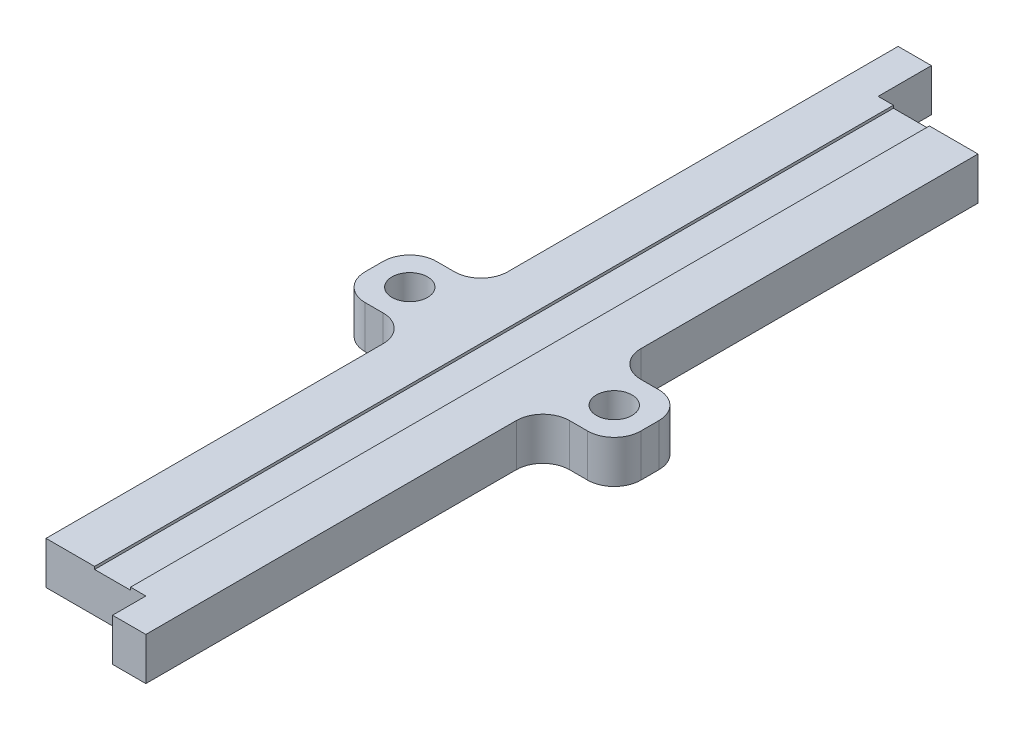
SolidWorks part; units mm, degrees
ref_plane "Front Plane" through (0, 0, 0) normal (0, 0, 1) x (1, 0, 0)
ref_plane "Top Plane" through (0, 0, 0) normal (0, 1, 0) x (1, 0, 0)
ref_plane "Right Plane" through (0, 0, 0) normal (1, 0, 0) x (0, 0, -1)
sketch "Sketch1" plane through (0, 0, 0) normal (0, 0, 1) x (1, 0, 0)
  line L1 (-6.35, -2.032) -> (6.35, -2.032)
  line L2 (-6.35, -2.032) -> (-6.35, 2.032)
  line L3 (-6.35, 2.032) -> (6.35, 2.032)
  line L4 (6.35, -2.032) -> (6.35, 2.032)
  line L5 (-6.35, -2.032) -> (6.35, 2.032) construction
  line L6 (-6.35, 2.032) -> (6.35, -2.032) construction
  point P0 (0, 0)
  dimension "D1" = 4.064
  dimension "D2" = 12.7
extrude "Boss-Extrude1" add sketch "Sketch1" along normal blind 228.6
sketch "Sketch2" plane through (0, 2.032, 0) normal (0, 1, 0) x (1, 0, 0)
  line L0 (1.7145, -114.3) -> (6.35, -114.3) construction
  line L1 (-1.7145, -5.6134) -> (1.7145, -5.6134)
  line L2 (-1.7145, -5.6134) -> (-1.7145, -222.9866)
  line L3 (-1.7145, -222.9866) -> (1.7145, -222.9866)
  line L4 (1.7145, -5.6134) -> (1.7145, -222.9866)
  line L5 (6.35, -228.6) -> (6.35, 0) construction
  line L6 (-1.7145, -114.3) -> (-6.35, -114.3) construction
  line L7 (-6.35, -228.6) -> (-6.35, 0) construction
  dimension "D1" = 3.429
  dimension "D2" = 217.3732
extrude "Cut-Extrude1" cut sketch "Sketch2" against normal blind 0.254
sketch "Sketch3" plane through (0, 2.032, 0) normal (0, 1, 0) x (1, 0, 0)
  line L1 (-6.35, -228.6) -> (-5.842, -228.6)
  line L2 (-6.35, -228.6) -> (-6.35, -223.52)
  line L3 (-6.35, -223.52) -> (-5.842, -223.52)
  line L4 (-5.842, -228.6) -> (-5.842, -223.52)
  dimension "D1" = 0.508
  dimension "D2" = 5.08
extrude "Cut-Extrude2" cut sketch "Sketch3" against normal through all
ref_plane "Plane1" through (0, 0, 114.3) normal (0, 0, -1) x (-1, 0, 0)
mirror "Mirror1" about plane through (0, 0, 114.3) normal (0, 0, -1) of "Cut-Extrude2"
mirror "Mirror2" about plane through (0, 0, 0) normal (1, 0, 0) of "Mirror1", "Cut-Extrude2"
sketch "Sketch4" plane through (0, 2.032, 0) normal (0, 1, 0) x (1, 0, 0)
  line L2 (-5.842, -228.6) -> (-2.667, -228.6)
  line L3 (-5.842, -228.6) -> (-5.842, -225.425)
  line L4 (-5.842, -225.425) -> (-2.667, -225.425)
  line L5 (-2.667, -228.6) -> (-2.667, -225.425)
  dimension "D1" = 3.175
  dimension "D2" = 3.175
extrude "Cut-Extrude3" cut sketch "Sketch4" against normal through all
sketch "Sketch5" plane through (0, 2.032, 0) normal (0, 1, 0) x (1, 0, 0)
  line L0 (5.842, 0) -> (-5.842, 0) construction
  line L1 (-6.35, 0) -> (6.35, 0)
  line L2 (-6.35, 0) -> (-6.35, -152.4) construction
  line L3 (-6.35, -152.4) -> (6.35, -152.4) construction
  line L4 (6.35, 0) -> (6.35, -152.4) construction
  line L5 (5.842, -228.6) -> (-2.667, -228.6) construction
  line L6 (-6.35, -223.52) -> (-6.35, -5.08) construction
  line L7 (6.35, -223.52) -> (6.35, -5.08) construction
  line L8 (-6.35, -152.4) -> (3.175, -152.4)
  line L9 (3.175, -152.4) -> (3.175, -155.575)
  line L10 (3.175, -155.575) -> (6.35, -155.575)
  line L11 (6.35, -155.575) -> (6.35, -152.4) construction
  line L12 (-6.35, -152.4) -> (-6.35, -228.6)
  line L13 (-6.35, -228.6) -> (6.35, -228.6)
  line L14 (6.35, -228.6) -> (6.35, -155.575)
  line L15 (-6.35, 0) -> (-6.35, -71.12)
  line L16 (-3.175, -71.12) -> (-3.175, -76.2)
  line L17 (-3.175, -76.2) -> (6.35, -76.2)
  line L18 (6.35, -76.2) -> (6.35, 0)
  line L19 (-6.35, -71.12) -> (-3.175, -71.12)
  dimension "D1" = 0
  dimension "D2" = 76.2
  dimension "D3" = 0
  dimension "D4" = 0
  dimension "D5" = 3.175
  dimension "D6" = 3.175
  dimension "D7" = 5.08
  dimension "D8" = 3.175
  dimension "D9" = 76.2
extrude "Cut-Extrude5" cut sketch "Sketch5" against normal through all
sketch "Sketch6" plane through (0, 2.032, 0) normal (0, 1, 0) x (1, 0, 0)
  line L0 (-6.35, -152.4) -> (-6.35, -71.12) construction
  line L1 (-6.35, -110.8989) -> (-13.1521, -110.8989)
  line L2 (-6.35, -110.8989) -> (-6.35, -117.7011)
  line L3 (-6.35, -117.7011) -> (-13.1521, -117.7011)
  line L4 (-13.1521, -110.8989) -> (-13.1521, -117.7011)
  line L6 (-1.7145, -152.4) -> (-6.35, -152.4) construction
  line L7 (-6.35, -110.8989) -> (-13.1521, -110.8989)
  line L8 (-6.35, -117.7011) -> (-13.1521, -117.7011)
  line L9 (0, -76.2) -> (0, -152.4) construction
  line L10 (-13.1521, -114.3) -> (-9.7511, -114.3) construction
  line L11 (-1.7145, -76.2) -> (1.7145, -76.2) construction
  line L12 (1.7145, -152.4) -> (-1.7145, -152.4) construction
  line L13 (13.1521, -114.3) -> (9.7511, -114.3) construction
  line L14 (6.35, -117.7011) -> (13.1521, -117.7011)
  line L15 (6.35, -110.8989) -> (13.1521, -110.8989)
  line L16 (13.1521, -110.8989) -> (13.1521, -117.7011)
  line L17 (6.35, -117.7011) -> (13.1521, -117.7011)
  line L18 (6.35, -110.8989) -> (6.35, -117.7011)
  line L19 (6.35, -110.8989) -> (13.1521, -110.8989)
  circle A0 centre (-9.7511, -114.3) radius 1.7005
  circle A1 centre (9.7511, -114.3) radius 1.7005
  line M1 (-6.35, -71.12) -> (-6.35, -152.4)
  dimension "D3" = 3.4011
  dimension "D1" = 6.8021
  dimension "D2" = 3.4011
  dimension "D4" = 34.6989
extrude "Boss-Extrude2" add sketch "Sketch6" against normal through all contours L1 L4 L3 A0 M1 | L15 L18 L14 L16 A1
fillet "Fillet1" radius 2.54 8 edges at (13.1521, 0, 110.8989) (13.1521, 0, 117.7011) (-13.1521, 0, 117.7011) (-13.1521, 0, 110.8989)
equation "\"D2@Sketch6\"=\"D1@Sketch6\"/2"
